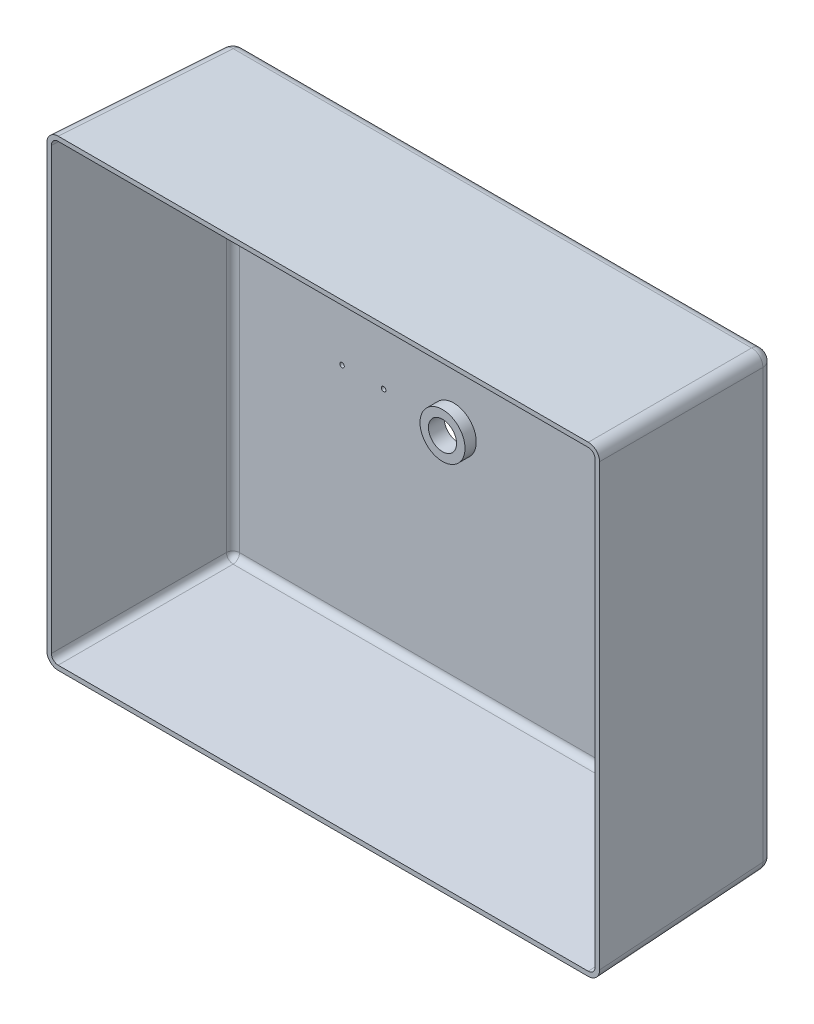
SolidWorks part; units mm, degrees
material "1060 Alloy"
ref_plane "Front" through (0, 0, 0) normal (0, 0, 1) x (1, 0, 0)
ref_plane "Top" through (0, 0, 0) normal (0, 1, 0) x (1, 0, 0)
ref_plane "Right" through (0, 0, 0) normal (1, 0, 0) x (0, 0, -1)
sketch "Sketch1" plane through (0, 0, 0) normal (0, 0, 1) x (1, 0, 0)
  line L1 (0, 0) -> (609.6, 0)
  line L2 (0, 0) -> (0, 508)
  line L3 (0, 508) -> (609.6, 508)
  line L4 (609.6, 0) -> (609.6, 508)
extrude "Extrude1" add sketch "Sketch1" along normal blind 203.2 draft 2 draft outward yes
fillet "Fillet1" radius 12.7 8 edges at (-3.548, -3.548, 101.6) (613.148, -3.548, 101.6) (-3.548, 511.548, 101.6) (613.148, 511.548, 101.6) (0, 254, 0) (609.6, 254, 0) (304.8, 508, 0) (304.8, 0, 0)
shell "Shell1" thickness 5.08
sketch "Sketch2" plane through (0, 0, 0) normal (0, 0, -1) x (-1, 0, 0)
  circle A0 centre (-558.8, 50.8) radius 25.4
  circle A1 centre (-50.8, 50.8) radius 25.4
  circle A2 centre (-558.8, 457.2) radius 25.4
  circle A3 centre (-50.8, 457.2) radius 25.4
extrude "Extrude2" add sketch "Sketch2" along normal blind 12.7 draft 2
fillet "Fillet2" radius 2.54 8 edges at (25.4, 50.8, 0) (25.8435, 50.8, -12.7) (533.8435, 50.8, -12.7) (533.4, 50.8, 0) (25.4, 457.2, 0) (25.8435, 457.2, -12.7) (533.4, 457.2, 0) (533.8435, 457.2, -12.7)
sketch "Sketch3" plane through (0, 0, 5.08) normal (0, 0, 1) x (1, 0, 0)
  circle A0 centre (254, 254) radius 25.4
extrude "Extrude3" add sketch "Sketch3" along normal blind 12.7
hole_wizard "1 (1) Diameter Hole1" positions "3DSketch1" profile "Sketch5" hole size "1" standard "Ansi Inch" end condition through all
sketch3d "3DSketch1"
  point P0 (254, 254, 17.78)
sketch "Sketch5" plane through (254, 254, 17.78) normal (1, 0, 0) x (0, -1, 0)
  line L0 (0, 0) -> (0, 30.48)
  line L1 (0, 30.48) -> (15.875, 30.48)
  line L2 (15.875, 30.48) -> (15.875, 0)
  line L5 (15.875, 0) -> (0, 0)
  line L11 (0, -6.35) -> (0, 107.95) construction
  dimension "Thru Hole Dia." = 31.75
  dimension "Thru Hole Depth" = 30.48
hole_wizard "3/8 (0.375) Diameter Hole1" positions "3DSketch2" profile "Sketch6" hole size "3/8" standard "Ansi Inch" end condition through all
sketch3d "3DSketch2"
  point P0 (508, 469.9, 5.08)
sketch "Sketch6" plane through (508, 469.9, 5.08) normal (1, 0, 0) x (0, -1, 0)
  line L0 (0, 0) -> (0, 17.78)
  line L1 (0, 17.78) -> (4.7625, 17.78)
  line L2 (4.7625, 17.78) -> (4.7625, 0)
  line L5 (4.7625, 0) -> (0, 0)
  line L11 (0, -6.35) -> (0, 107.95) construction
  dimension "Thru Hole Dia." = 9.525
  dimension "Thru Hole Depth" = 17.78
hole_wizard "3/8 (0.375) Diameter Hole2" positions "Sketch10" profile "Sketch9" hole size "3/8" standard "Ansi Inch"
sketch "Sketch10" plane through (0, 0, 5.08) normal (0, 0, 1) x (1, 0, 0)
  point P1 (508, 406.4)
sketch "Sketch9" plane through (508, 406.4, 5.08) normal (1, 0, 0) x (0, -1, 0)
  line L0 (0, 0) -> (0, 20.6416)
  line L1 (0, 20.6416) -> (4.7625, 17.78)
  line L2 (4.7625, 17.78) -> (4.7625, 0)
  line L5 (4.7625, 0) -> (0, 0)
  line L10 (0, 20.6416) -> (-4.7625, 17.78) construction
  line L11 (0, -6.35) -> (0, 107.95) construction
  dimension "Hole Dia." = 9.525
  dimension "Hole Depth" = 17.78
  dimension "Drill Angle" = 118
pattern_circular "CirPattern1" count 3 over 360 about axis through (508, 406.4, 0) along (0, 0, 1) of "3/8 (0.375) Diameter Hole1"
sketch "Sketch11" plane through (0, 0, 0) normal (0, 0, -1) x (-1, 0, 0)
  line L0 (-50.8, 50.8) -> (-50.8, 253.4209) construction
  line L1 (-50.8, 253.4209) -> (-127.9068, 253.4209) construction
  point P0 (-127.9068, 253.4209)
hole_wizard "#10 Clearance Hole1" positions "3DSketch3" profile "Sketch12" hole size "#10" standard "Ansi Inch" end condition through all
sketch3d "3DSketch3"
  point P0 (127.9068, 253.4209, 0)
sketch "Sketch12" plane through (127.9068, 253.4209, 0) normal (1, 0, 0) x (0, 1, 0)
  line L0 (0, 0) -> (0, 203.2)
  line L1 (0, 203.2) -> (2.5527, 203.2)
  line L2 (2.5527, 203.2) -> (2.5527, 0)
  line L5 (2.5527, 0) -> (0, 0)
  line L11 (0, -6.35) -> (0, 107.95) construction
  dimension "Thru Hole Dia." = 5.1054
  dimension "Thru Hole Depth" = 203.2
pattern_linear "LPattern1" count 2 spacing 46.99 along (1, 0, 0) of "#10 Clearance Hole1"
